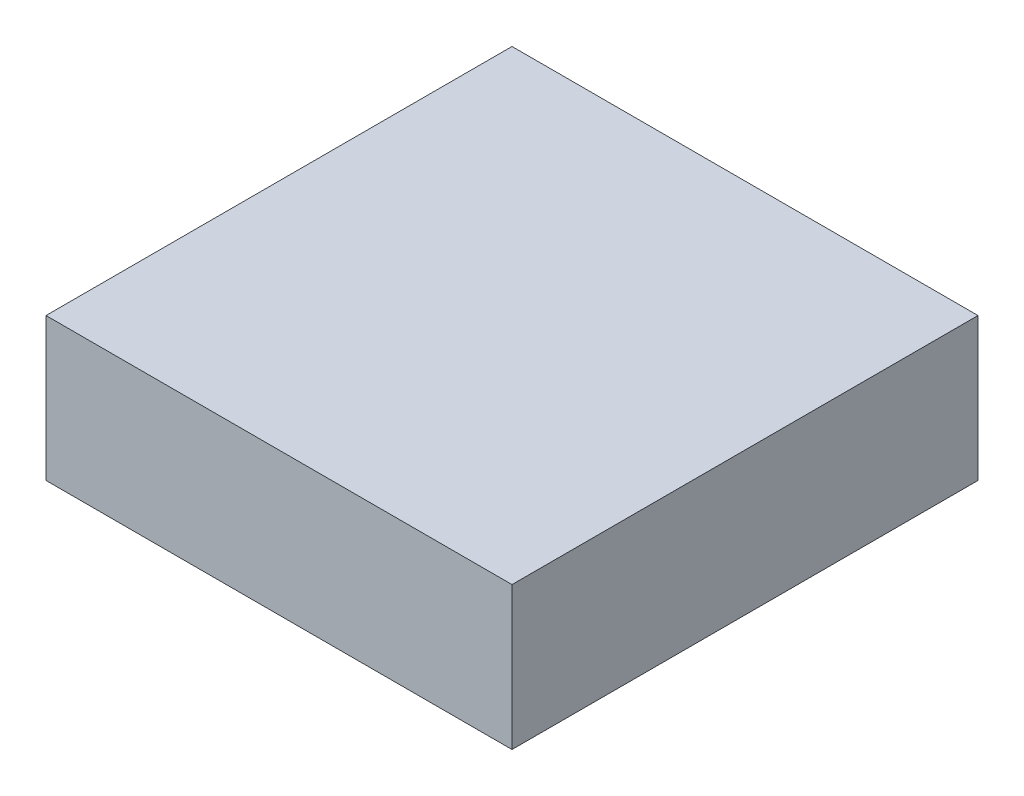
SolidWorks part; units mm, degrees
ref_plane "Front Plane" through (0, 0, 0) normal (0, 0, 1) x (1, 0, 0)
ref_plane "Top Plane" through (0, 0, 0) normal (0, 1, 0) x (1, 0, 0)
ref_plane "Right Plane" through (0, 0, 0) normal (1, 0, 0) x (0, 0, -1)
sketch "Sketch1" plane through (0, 0, 0) normal (0, 0, 1) x (1, 0, 0)
  line L1 (-35.7, -10.945) -> (35.7, -10.945)
  line L2 (-35.7, -10.945) -> (-35.7, 10.945)
  line L3 (-35.7, 10.945) -> (35.7, 10.945)
  line L4 (35.7, -10.945) -> (35.7, 10.945)
  line L5 (-35.7, -10.945) -> (35.7, 10.945) construction
  line L6 (-35.7, 10.945) -> (35.7, -10.945) construction
  point P0 (0, 0)
extrude "Envelope" add sketch "Sketch1" along normal blind 71.4
